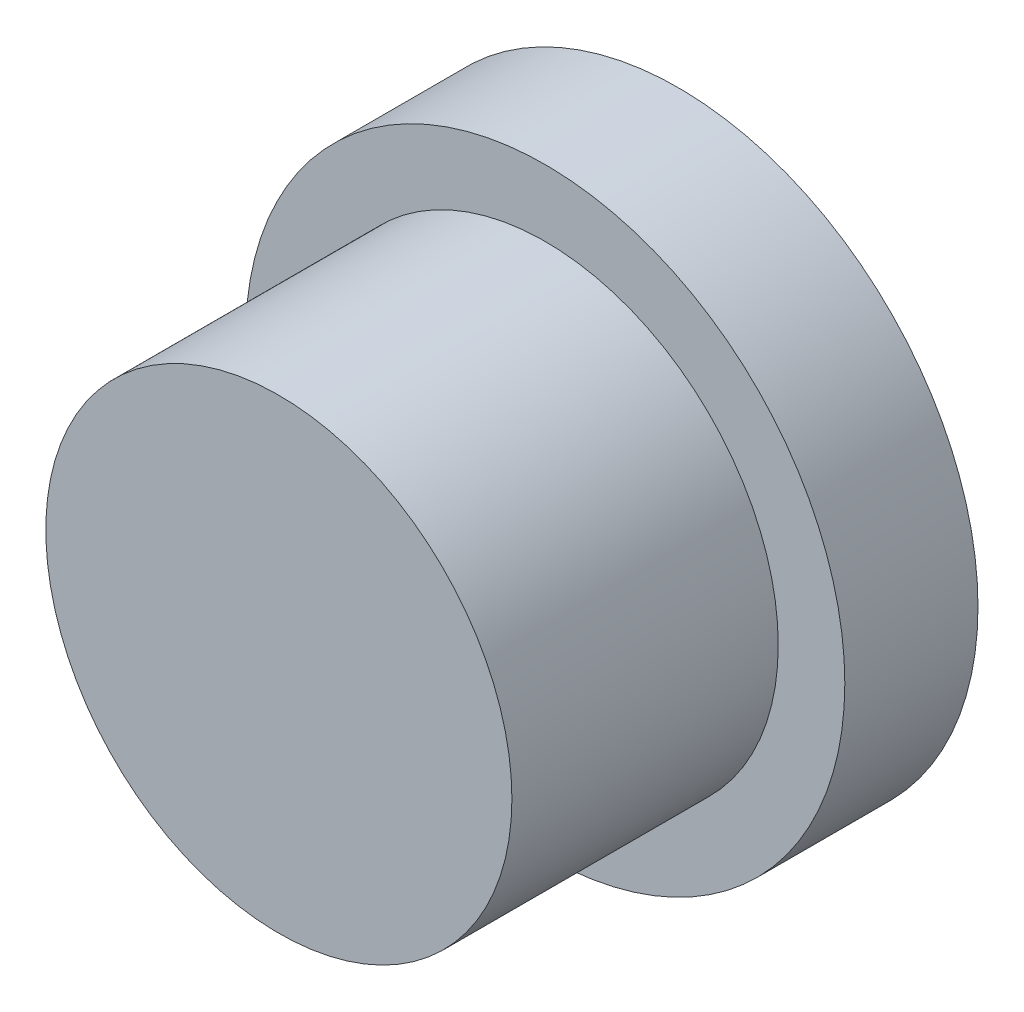
SolidWorks part; units mm, degrees
material "ABS"
ref_plane "Спереди" through (0, 0, 0) normal (0, 0, 1) x (1, 0, 0)
ref_plane "Сверху" through (0, 0, 0) normal (0, 1, 0) x (1, 0, 0)
ref_plane "Справа" through (0, 0, 0) normal (1, 0, 0) x (0, 0, -1)
sketch "Эскиз1" plane through (0, 0, 0) normal (0, 0, 1) x (1, 0, 0)
  circle A0 centre (0, 0) radius 4.5
  dimension "D1" = 9
extrude "Бобышка-Вытянуть1" add sketch "Эскиз1" along normal blind 2 contours A0
sketch "Эскиз2" plane through (0, 0, 2) normal (0, 0, 1) x (1, 0, 0)
  circle A0 centre (0, 0) radius 3.5
  dimension "D1" = 7
extrude "Бобышка-Вытянуть2" add sketch "Эскиз2" along normal blind 4
sketch "Эскиз3" plane through (0, 0, 0) normal (0, 0, -1) x (-1, 0, 0)
  circle A0 centre (0, 0) radius 2.5
  point P2 (0.8731, 1.2054)
  dimension "D1" = 5
extrude "Вырез-Вытянуть1" cut sketch "Эскиз3" against normal blind 5
